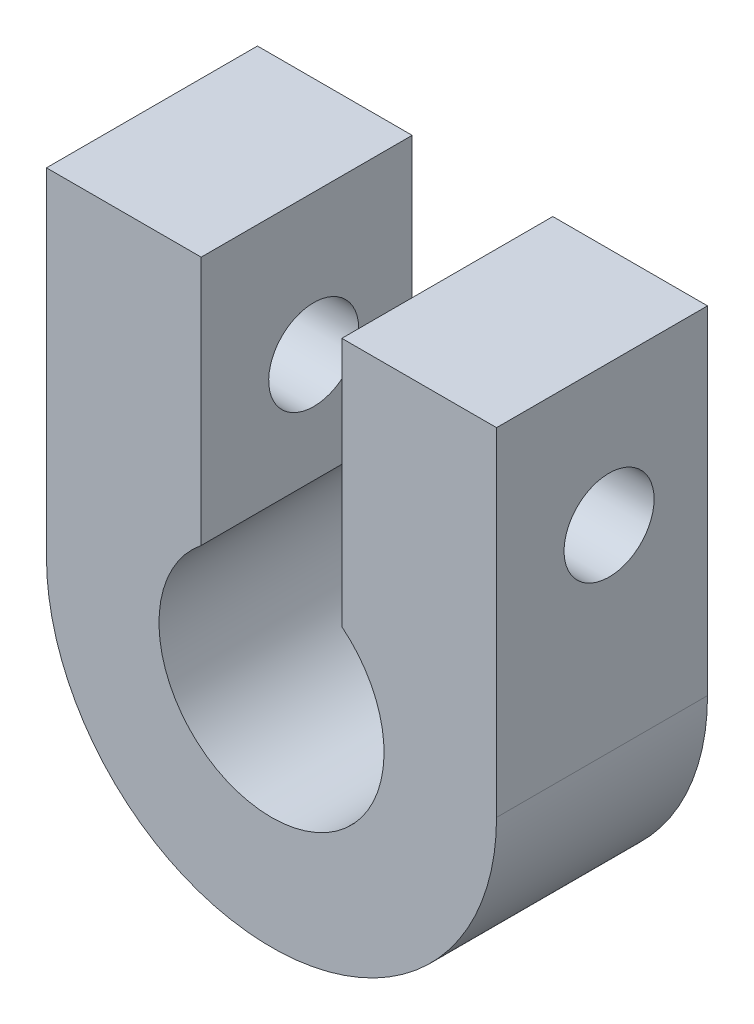
SolidWorks part; units mm, degrees
material "ABS"
ref_plane "Front Plane" through (0, 0, 0) normal (0, 0, 1) x (1, 0, 0)
ref_plane "Top Plane" through (0, 0, 0) normal (0, 1, 0) x (1, 0, 0)
ref_plane "Right Plane" through (0, 0, 0) normal (1, 0, 0) x (0, 0, -1)
ref_plane "Plane1" through (0, 0, 8) normal (0, 0, 1) x (1, 0, 0)
sketch "Sketch1" plane through (0, 0, 8) normal (0, 0, 1) x (1, 0, 0)
  line L0 (8, 0) -> (8, 12)
  line L1 (8, 12) -> (-8, 12)
  line L2 (-8, 12) -> (-8, 0)
  arc A0 (-8, 0) -> (8, 0) centre (0, 0) ccw
extrude "Boss-Extrude1" add sketch "Sketch1" against normal blind 8
sketch "Sketch2" plane through (0, 0, 0) normal (0, 0, -1) x (-1, 0, 0)
  line L0 (2.5, 12) -> (-2.5, 12)
  line L1 (-2.5, 12) -> (-2.5, 3.1225)
  line L2 (2.5, 3.1225) -> (2.5, 12)
  arc A0 (-2.5, 3.1225) -> (2.5, 3.1225) centre (0, 0) cw
extrude "Cut-Extrude1" cut sketch "Sketch2" against normal through all
sketch "Sketch3" plane through (-8, 0, 0) normal (-1, 0, 0) x (0, 0, 1)
  line L0 (5.6743, 4.1) -> (7.3486, 7)
  line L1 (7.3486, 7) -> (5.6743, 9.9)
  line L2 (5.6743, 9.9) -> (2.3257, 9.9)
  line L3 (2.3257, 9.9) -> (0.6514, 7)
  line L4 (0.6514, 7) -> (2.3257, 4.1)
  line L5 (2.3257, 4.1) -> (5.6743, 4.1)
extrude "Cut-Extrude2" cut sketch "Sketch3" against normal blind 1.99
sketch "Sketch5" plane through (8, 0, 0) normal (1, 0, 0) x (0, 0, -1)
  line L0 (-5.3304, 6.1111) -> (-5.1314, 5.8686)
  line L1 (-5.1314, 5.8686) -> (-4.8889, 5.6696)
  line L2 (-4.8889, 5.6696) -> (-4.6123, 5.5218)
  line L3 (-4.6123, 5.5218) -> (-4.3121, 5.4307)
  line L4 (-4.3121, 5.4307) -> (-4, 5.4)
  line L5 (-4, 5.4) -> (-3.6879, 5.4307)
  line L6 (-3.6879, 5.4307) -> (-3.3877, 5.5218)
  line L7 (-3.3877, 5.5218) -> (-3.1111, 5.6696)
  line L8 (-3.1111, 5.6696) -> (-2.8686, 5.8686)
  line L9 (-2.8686, 5.8686) -> (-2.6696, 6.1111)
  line L10 (-2.6696, 6.1111) -> (-2.5218, 6.3877)
  line L11 (-2.5218, 6.3877) -> (-2.4307, 6.6879)
  line L12 (-2.4307, 6.6879) -> (-2.4, 7)
  line L13 (-2.4, 7) -> (-2.4307, 7.3121)
  line L14 (-2.4307, 7.3121) -> (-2.5218, 7.6123)
  line L15 (-2.5218, 7.6123) -> (-2.6696, 7.8889)
  line L16 (-2.6696, 7.8889) -> (-2.8686, 8.1314)
  line L17 (-2.8686, 8.1314) -> (-3.1111, 8.3304)
  line L18 (-3.1111, 8.3304) -> (-3.3877, 8.4782)
  line L19 (-3.3877, 8.4782) -> (-3.6879, 8.5693)
  line L20 (-3.6879, 8.5693) -> (-4, 8.6)
  line L21 (-4, 8.6) -> (-4.3121, 8.5693)
  line L22 (-4.3121, 8.5693) -> (-4.6123, 8.4782)
  line L23 (-4.6123, 8.4782) -> (-4.8889, 8.3304)
  line L24 (-4.8889, 8.3304) -> (-5.1314, 8.1314)
  line L25 (-5.1314, 8.1314) -> (-5.3304, 7.8889)
  line L26 (-5.3304, 7.8889) -> (-5.4782, 7.6123)
  line L27 (-5.4782, 7.6123) -> (-5.5693, 7.3121)
  line L28 (-5.5693, 7.3121) -> (-5.6, 7)
  line L29 (-5.6, 7) -> (-5.5693, 6.6879)
  line L30 (-5.5693, 6.6879) -> (-5.4782, 6.3877)
  line L31 (-5.4782, 6.3877) -> (-5.3304, 6.1111)
extrude "Cut-Extrude4" cut sketch "Sketch5" against normal up to next
sketch "Sketch6" plane through (0, 0, 0) normal (0, 1, 0) x (1, 0, 0)
  line L0 (4, 0) -> (0, 0)
  line L1 (0, 0) -> (0, -8)
  line L2 (0, -8) -> (4, -8)
  line L3 (4, -8) -> (4, 0)
  line L4 (0, 0) -> (0, -8) construction
revolve "Cut-Revolve1" cut sketch "Sketch6" angle 360 about L4
sketch "Sketch7" plane through (8, 0, 0) normal (1, 0, 0) x (0, 0, -1)
  circle A0 centre (-4, 7) radius 1.6
extrude "Cut-Extrude5" cut sketch "Sketch7" against normal through all
chamfer "Chamfer1" distance 0.5 angle 45 8 edges at (-2.5, 7.5612, 0) (0, -4, 0) (2.5, 7.5612, 0) (-5.25, 12, 0) (-8, 6, 0) (0, -8, 0) (8, 6, 0) (5.25, 12, 0)
